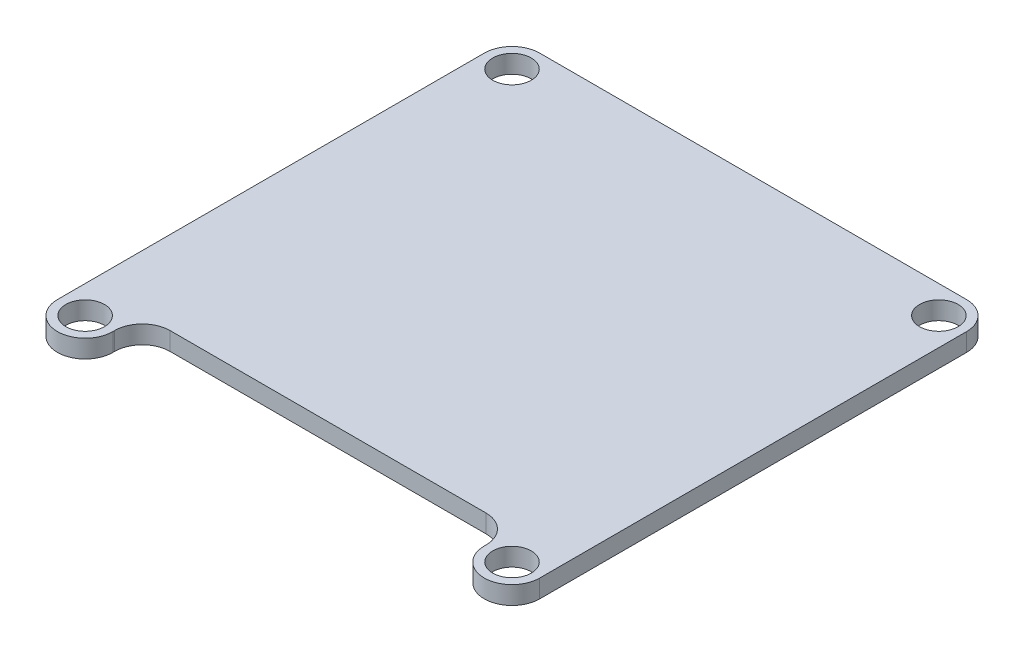
SolidWorks part; units mm, degrees
ref_plane "Front Plane" through (0, 0, 0) normal (0, 0, 1) x (1, 0, 0)
ref_plane "Top Plane" through (0, 0, 0) normal (0, 1, 0) x (1, 0, 0)
ref_plane "Right Plane" through (0, 0, 0) normal (1, 0, 0) x (0, 0, -1)
sketch "Sketch1" plane through (0, 0, 0) normal (0, 1, 0) x (1, 0, 0)
  line L1 (-18.944, 12.823) -> (16.456, 12.823)
  line L2 (-21.244, 10.523) -> (-21.244, -24.877)
  line L4 (18.756, 10.523) -> (18.756, -24.877)
  line L6 (-16.644, -24.877) -> (-16.644, -24.7337)
  line L7 (-14.344, -22.4337) -> (11.856, -22.4337)
  line L8 (14.156, -24.877) -> (14.156, -24.7337)
  arc A0 (-18.944, -27.177) -> (-21.244, -24.877) centre (-18.944, -24.877) cw
  arc A1 (16.456, -27.177) -> (18.756, -24.877) centre (16.456, -24.877) ccw
  arc A2 (18.756, 10.523) -> (16.456, 12.823) centre (16.456, 10.523) ccw
  arc A3 (-21.244, 10.523) -> (-18.944, 12.823) centre (-18.944, 10.523) cw
  arc A4 (11.856, -22.4337) -> (14.156, -24.7337) centre (11.856, -24.7337) cw
  arc A5 (-14.344, -22.4337) -> (-16.644, -24.7337) centre (-14.344, -24.7337) ccw
  arc A6 (-18.944, -27.177) -> (-16.644, -24.877) centre (-18.944, -24.877) ccw
  arc A7 (16.456, -27.177) -> (14.156, -24.877) centre (16.456, -24.877) cw
  dimension "D3" = 2.3
  dimension "D6" = 2.3
  dimension "D1" = 40
  dimension "D4" = 4.6
  dimension "D5" = 4.6
extrude "Boss-Extrude1" add sketch "Sketch1" along normal blind 1.5
hole_wizard "Ø3.2 (3.2) Diameter Hole1" positions "Sketch2" profile "Sketch3" hole size "Ø3.2" standard "ANSI Metric" end condition through all
sketch "Sketch2" plane through (0, 1.5, 0) normal (0, 1, 0) x (1, 0, 0)
  point P0 (-18.944, 10.523)
  point P3 (16.456, 10.523)
  point P6 (16.456, -24.877)
  point P9 (-18.944, -24.877)
sketch "Sketch3" plane through (-18.944, 1.5, -10.523) normal (1, 0, 0) x (0, 0, 1)
  line L0 (0, 0) -> (0, 1.5)
  line L1 (0, 1.5) -> (1.6, 1.5)
  line L2 (1.6, 1.5) -> (1.6, 0)
  line L5 (1.6, 0) -> (0, 0)
  line L11 (0, -6.35) -> (0, 107.95) construction
  dimension "Thru Hole Dia." = 3.2
  dimension "Thru Hole Depth" = 1.5
